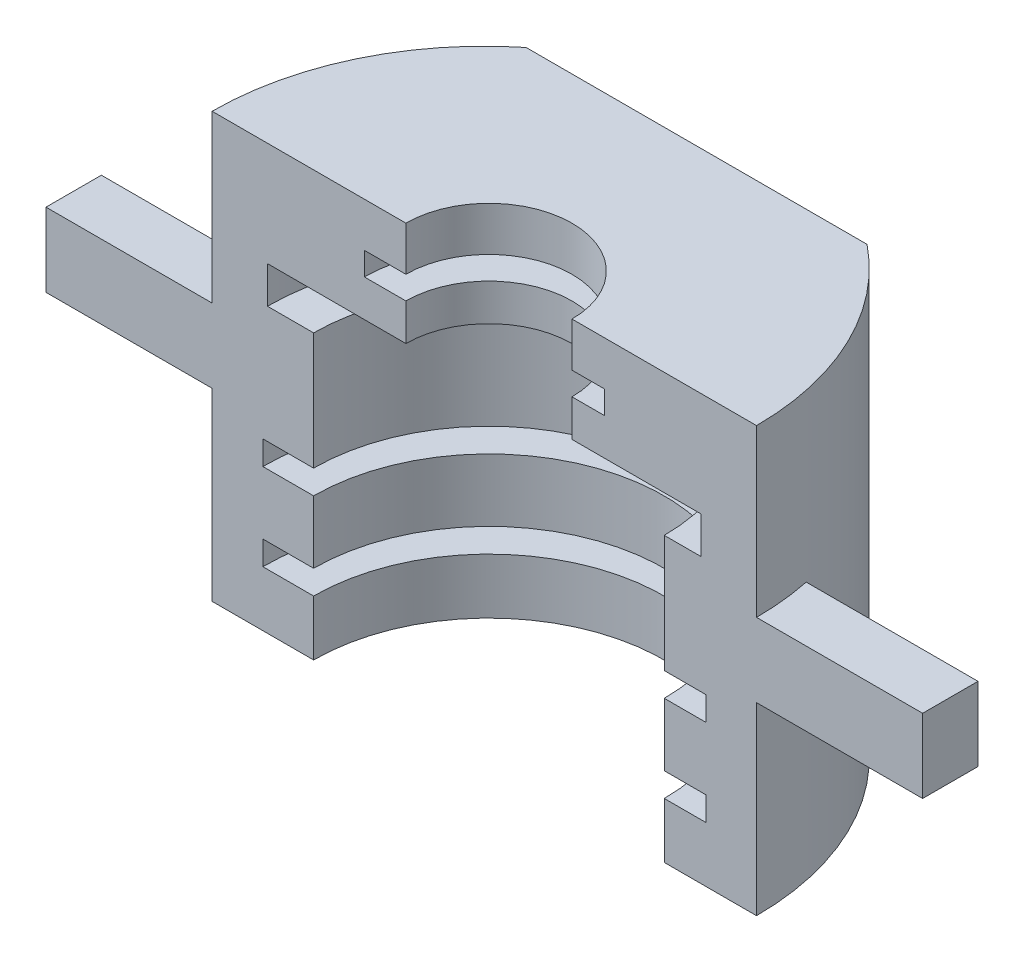
SolidWorks part; units mm, degrees
ref_plane "Alzado" through (0, 0, 0) normal (0, 0, 1) x (1, 0, 0)
ref_plane "Planta" through (0, 0, 0) normal (0, 1, 0) x (1, 0, 0)
ref_plane "Vista lateral" through (0, 0, 0) normal (1, 0, 0) x (0, 0, -1)
sketch "Croquis1" plane through (0, 0, 0) normal (0, 0, 1) x (1, 0, 0)
  line L0 (-91.6288, 0) -> (-106.1288, 0)
  line L1 (-106.1288, 0) -> (-106.1288, 23)
  line L2 (-106.1288, 23) -> (-91.3788, 23)
  line L3 (-91.6288, 0) -> (-91.6288, 3.003)
  line L4 (-91.6288, 4.303) -> (-91.6288, 7.703)
  line L5 (-91.6288, 3.003) -> (-103.3788, 3.003)
  line L6 (-91.6288, 15.35) -> (-91.6288, 9.003)
  line L7 (-91.6288, 4.303) -> (-103.3788, 4.303)
  line L8 (-103.3788, 3.003) -> (-103.3788, 4.303)
  line L9 (-91.6288, 7.703) -> (-103.3788, 7.703)
  line L10 (-91.3788, 20.6) -> (-91.3788, 23)
  line L11 (-91.6288, 9.003) -> (-103.3788, 9.003)
  line L12 (-103.3788, 7.703) -> (-103.3788, 9.003)
  line L13 (-91.3788, 19.35) -> (-97.8788, 19.35)
  line L14 (-91.3788, 17.35) -> (-103.1288, 17.35)
  line L15 (-91.3788, 20.6) -> (-97.8788, 20.6)
  line L16 (-97.8788, 19.35) -> (-97.8788, 20.6)
  line L17 (-103.1288, 17.35) -> (-103.1288, 15.35)
  line L18 (-103.1288, 15.35) -> (-91.6288, 15.35)
  line L21 (-91.3788, 17.35) -> (-91.3788, 19.35)
  dimension "D1" = 14.5
  dimension "D2" = 23
  dimension "D3" = 1.3
  dimension "D4" = 11.75
  dimension "D5" = 3.4
  dimension "D6" = 1.3
  dimension "D7" = 10.35
  dimension "D8" = 1.25
  dimension "D9" = 6.5
  dimension "D10" = 2
  dimension "D11" = 2
revolve "Revolución1" add sketch "Croquis1" angle 180 about L21
sketch "Croquis2" plane through (0, 0, 0) normal (0, -1, 0) x (1, 0, 0)
  line L1 (-100.6288, 0) -> (-81.6288, 0)
  arc A1 (-100.6288, 0) -> (-81.6288, 0) centre (-91.1288, 0) ccw
extrude "Cortar-Extruir1" cut sketch "Croquis2" against normal blind 17
sketch "Croquis3" plane through (0, 23, 0) normal (0, 1, 0) x (1, 0, 0)
  line L1 (-86.6288, 0) -> (-95.6288, 0)
  arc A1 (-86.6288, 0) -> (-95.6288, 0) centre (-91.1288, 0) ccw
extrude "Cortar-Extruir2" cut sketch "Croquis3" against normal up to vertex
sketch "Croquis4" plane through (0, 0, 0) normal (0, -1, 0) x (1, 0, 0)
  line L2 (-81.4751, -11.5) -> (-101.5121, -11.5)
  line L3 (-81.4751, -11.5) -> (-81.4751, -14.8103)
  line L4 (-81.4751, -14.8103) -> (-101.5121, -14.8103)
  line L5 (-101.5121, -11.5) -> (-101.5121, -14.8103)
extrude "Cortar-Extruir3" cut sketch "Croquis4" against normal up to vertex
sketch "Croquis5" plane through (0, 0, 0) normal (0, 0, 1) x (1, 0, 0)
  line L0 (-106.1288, 23) -> (-106.1288, 0) construction
  line L1 (-106.1288, 10) -> (-105.1288, 10)
  line L2 (-106.1288, 10) -> (-106.1288, 14)
  line L3 (-106.1288, 14) -> (-105.1288, 14)
  line L4 (-105.1288, 10) -> (-105.1288, 14)
  line L5 (-100.6288, 0) -> (-106.1288, 0) construction
  line L6 (-76.6288, 23) -> (-76.6288, 0) construction
  line L7 (-76.6288, 10) -> (-77.6288, 10)
  line L8 (-76.6288, 10) -> (-76.6288, 14)
  line L9 (-76.6288, 14) -> (-77.6288, 14)
  line L10 (-77.6288, 10) -> (-77.6288, 14)
  dimension "D1" = 10
  dimension "D2" = 4
  dimension "D3" = 1
  dimension "D4" = 1
extrude "Cortar-Extruir4" cut sketch "Croquis5" against normal blind 3
sketch "Croquis6" plane through (0, 0, 0) normal (0, 0, 1) x (1, 0, 0)
  line L1 (-105.1288, 10) -> (-115.1288, 10)
  line L2 (-105.1288, 10) -> (-105.1288, 14)
  line L3 (-105.1288, 14) -> (-115.1288, 14)
  line L4 (-115.1288, 10) -> (-115.1288, 14)
  line L5 (-77.6288, 10) -> (-67.6288, 10)
  line L6 (-77.6288, 10) -> (-77.6288, 14)
  line L7 (-77.6288, 14) -> (-67.6288, 14)
  line L8 (-67.6288, 10) -> (-67.6288, 14)
  dimension "D1" = 10
  dimension "D2" = 10
extrude "Saliente-Extruir1" add sketch "Croquis6" against normal blind 3
